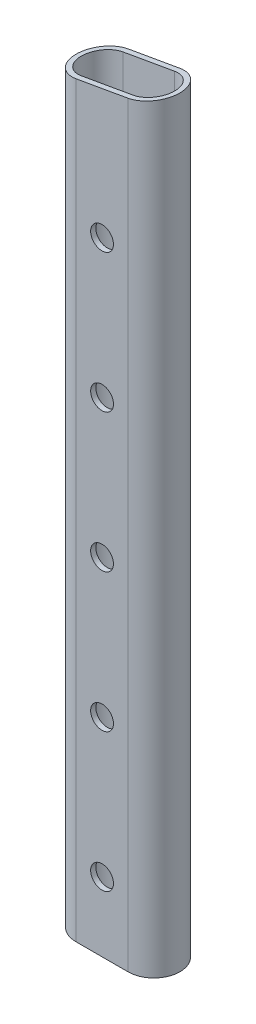
SolidWorks part; units mm, degrees
material "Простая углеродистая сталь"
ref_plane "Спереди" through (0, 0, 0) normal (0, 0, 1) x (1, 0, 0)
ref_plane "Сверху" through (0, 0, 0) normal (0, 1, 0) x (1, 0, 0)
ref_plane "Справа" through (0, 0, 0) normal (1, 0, 0) x (0, 0, -1)
sketch "Эскиз1" plane through (0, 0, 0) normal (0, 1, 0) x (1, 0, 0)
  line L0 (-7.5, 0) -> (7.5, 0) construction
  line L1 (-7.5, 7.5) -> (7.5, 7.5)
  line L2 (-7.5, -7.5) -> (7.5, -7.5)
  line L3 (-7.5, 6) -> (7.5, 6)
  line L4 (-7.5, -6) -> (7.5, -6)
  arc A0 (-7.5, 7.5) -> (-7.5, -7.5) centre (-7.5, 0) ccw
  arc A1 (7.5, -7.5) -> (7.5, 7.5) centre (7.5, 0) ccw
  arc A2 (7.5, -6) -> (7.5, 6) centre (7.5, 0) ccw
  arc A3 (-7.5, 6) -> (-7.5, -6) centre (-7.5, 0) ccw
  point P3 (0, 0)
  dimension "D1" = 15
  dimension "D2" = 30
  dimension "D3" = 1.5
extrude "Бобышка-Вытянуть1" add sketch "Эскиз1" along normal blind 220
sketch "Эскиз2" plane through (0, 0, 7.5) normal (0, 0, 1) x (1, 0, 0)
  line L0 (15, 220) -> (-15, 220)
  line L1 (-15, 220) -> (-15, 214.7102)
  line L2 (-15, 214.7102) -> (15, 220)
  line L3 (15, 0) -> (15, 220) construction
  line L4 (-7.5, 220) -> (7.5, 220) construction
  line L5 (-15, 220) -> (-15, 0) construction
  line L6 (0, 220) -> (0, 180) construction
  line L7 (0, 180) -> (0, 140) construction
  line L8 (0, 140) -> (0, 100) construction
  line L9 (0, 100) -> (0, 60) construction
  line L10 (0, 60) -> (0, 20) construction
  circle A0 centre (0, 180) radius 3.3
  circle A1 centre (0, 140) radius 3.3
  circle A2 centre (0, 100) radius 3.3
  circle A3 centre (0, 60) radius 3.3
  circle A4 centre (0, 20) radius 3.3
  dimension "D4" = 6.6
  dimension "D1" = 10
  dimension "D2" = 40
  dimension "D3" = 40
extrude "Вырез-Вытянуть1" cut sketch "Эскиз2" against normal through all
